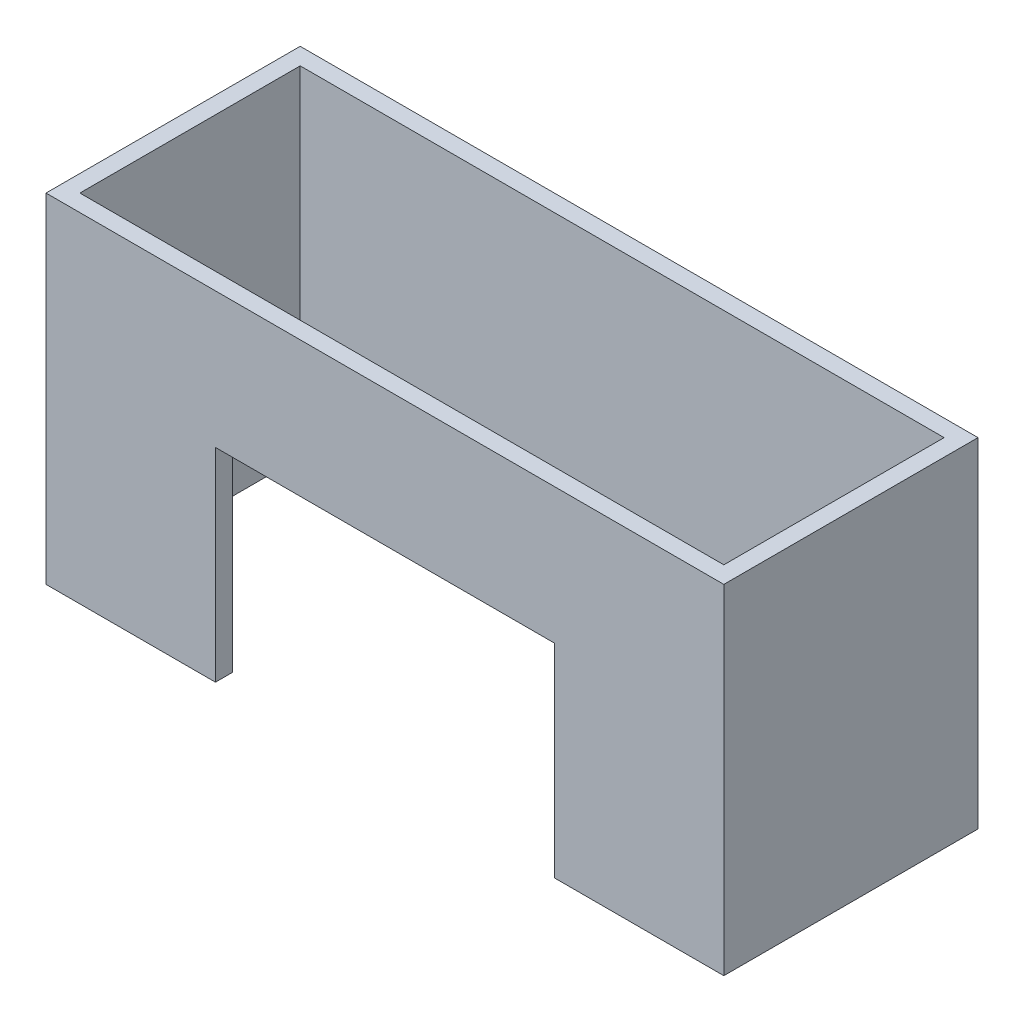
SolidWorks part; units mm, degrees
ref_plane "Front Plane" through (0, 0, 0) normal (0, 0, 1) x (1, 0, 0)
ref_plane "Top Plane" through (0, 0, 0) normal (0, 1, 0) x (1, 0, 0)
ref_plane "Right Plane" through (0, 0, 0) normal (1, 0, 0) x (0, 0, -1)
sketch "Sketch1" plane through (0, 0, 0) normal (0, 0, 1) x (1, 0, 0)
  line L1 (0, 0) -> (-400, 0)
  line L2 (0, 0) -> (0, 200)
  line L3 (0, 200) -> (-400, 200)
  line L4 (-400, 0) -> (-400, 200)
  dimension "D1" = 200
  dimension "D2" = 400
extrude "Boss-Extrude1" add sketch "Sketch1" along normal blind 150
sketch "Sketch2" plane through (0, 0, 150) normal (0, 0, 1) x (1, 0, 0)
  line L0 (-400, 0) -> (0, 0) construction
  line L1 (-300, 0) -> (-100, 0)
  line L2 (-300, 0) -> (-300, 120)
  line L3 (-300, 120) -> (-100, 120)
  line L4 (-100, 0) -> (-100, 120)
  dimension "D1" = 120
  dimension "D2" = 200
  dimension "D3" = 100
extrude "Cut-Extrude1" cut sketch "Sketch2" against normal blind 20
sketch "Sketch3" plane through (0, 200, 0) normal (0, 1, 0) x (1, 0, 0)
  line L0 (0, -150) -> (0, 0) construction
  line L1 (-10, -10) -> (-390, -10)
  line L2 (-10, -10) -> (-10, -140)
  line L3 (-10, -140) -> (-390, -140)
  line L4 (-390, -10) -> (-390, -140)
  line L5 (0, 0) -> (-400, 0) construction
  dimension "D1" = 130
  dimension "D2" = 380
  dimension "D3" = 10
  dimension "D4" = 10
extrude "Cut-Extrude2" cut sketch "Sketch3" against normal blind 200
